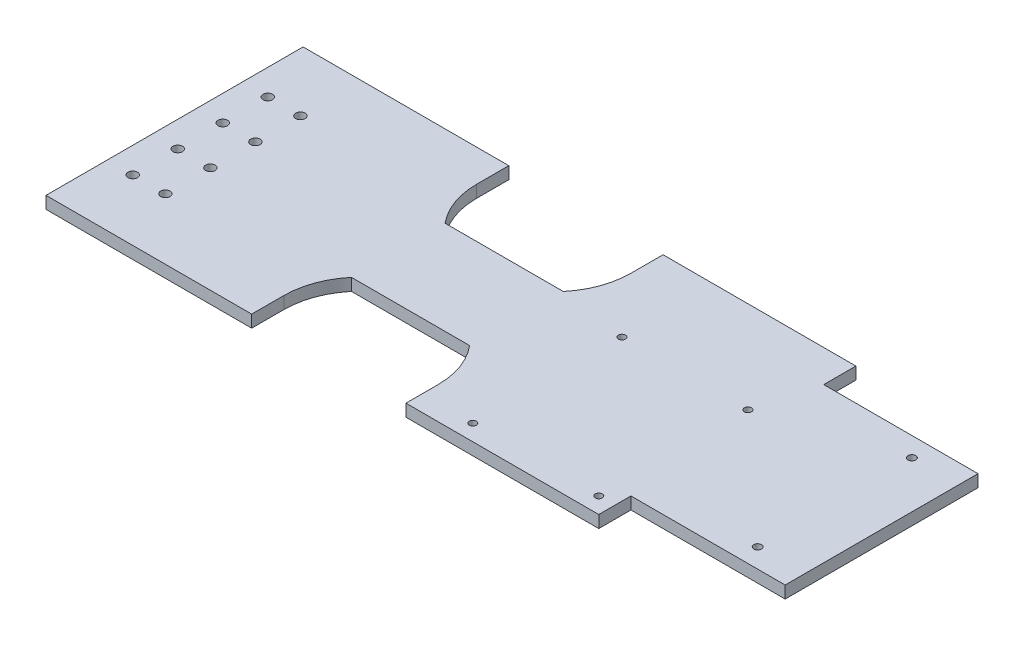
SolidWorks part; units mm, degrees
ref_plane "Front Plane" through (0, 0, 0) normal (0, 0, 1) x (1, 0, 0)
ref_plane "Top Plane" through (0, 0, 0) normal (0, 1, 0) x (1, 0, 0)
ref_plane "Right Plane" through (0, 0, 0) normal (1, 0, 0) x (0, 0, -1)
sketch "Sketch1" plane through (0, 0, 0) normal (0, 1, 0) x (1, 0, 0)
  line L0 (0, 0) -> (137.5, 0) construction
  line L1 (-137.5, 50) -> (137.5, 50)
  line L2 (-137.5, 50) -> (-137.5, -50)
  line L3 (-137.5, -50) -> (137.5, -50)
  line L4 (137.5, 50) -> (137.5, -50)
  line L5 (-137.5, 50) -> (137.5, -50) construction
  line L6 (-137.5, -50) -> (137.5, 50) construction
  point P0 (0, 0)
  point P11 (119.5, 0)
  point P14 (107, 0)
  point P19 (107, 0)
  dimension "D4" = 18
  dimension "D1" = 275
  dimension "D2" = 100
extrude "Boss-Extrude4" add sketch "Sketch1" along normal blind 4.75
sketch "Sketch3" plane through (0, 4.75, 0) normal (0, 1, 0) x (1, 0, 0)
  line L0 (0, 0) -> (137.5, 0) construction
  line L1 (137.5, -50) -> (137.5, 50) construction
  line L2 (119.3, -31.5) -> (119.3, 31.5) construction
  line L3 (137.5, -50) -> (77.5, -50)
  line L4 (137.5, -50) -> (137.5, -37.5)
  line L5 (137.5, -37.5) -> (77.5, -37.5)
  line L6 (77.5, -50) -> (77.5, -37.5)
  line L7 (137.5, 50) -> (77.5, 50)
  line L8 (137.5, 50) -> (137.5, 37.5)
  line L9 (137.5, 37.5) -> (77.5, 37.5)
  line L10 (77.5, 50) -> (77.5, 37.5)
  line L11 (119.3, -30) -> (119.3, 30) construction
  line L12 (-137.5, -50) -> (137.5, -50) construction
  line L13 (2.5, -50) -> (-57.5, -50)
  line L14 (2.5, -50) -> (2.5, -37.5)
  line L16 (-57.5, -50) -> (-57.5, -37.5)
  line L17 (137.5, 50) -> (-137.5, 50) construction
  line L18 (2.5, 50) -> (-57.5, 50)
  line L19 (2.5, 50) -> (2.5, 37.5)
  line L21 (-57.5, 50) -> (-57.5, 37.5)
  line L22 (-27.5, -37.5) -> (-27.5, -50) construction
  line L23 (-27.5, 37.5) -> (-27.5, 50) construction
  line L24 (-4.5187, 18.2164) -> (-50.4813, 18.2164)
  line L25 (-50.4813, -18.2164) -> (-4.5187, -18.2164)
  circle A0 centre (119.3, -30) radius 1.5
  circle A2 centre (119.3, 30) radius 1.5
  arc A5 (2.5, 37.5) -> (-4.5187, 18.2164) centre (-27.5, 37.5) cw
  arc A6 (-57.5, 37.5) -> (-50.4813, 18.2164) centre (-27.5, 37.5) ccw
  arc A7 (2.5, -37.5) -> (-4.5187, -18.2164) centre (-27.5, -37.5) ccw
  arc A8 (-57.5, -37.5) -> (-50.4813, -18.2164) centre (-27.5, -37.5) cw
  point P24 (119.3, 0)
  point P35 (119.3, 0)
  dimension "D1" = 75
  dimension "D2" = 60
  dimension "D3" = 60
  dimension "D4" = 63
  dimension "D5" = 18.2
  dimension "D7" = 75
extrude "Cut-Extrude1" cut sketch "Sketch3" against normal blind 10
sketch "Sketch4" plane through (0, 4.75, 0) normal (0, 1, 0) x (1, 0, 0)
  line L0 (-137.5, -50) -> (-57.5, -50) construction
  line L1 (-137.5, 50) -> (-137.5, -50) construction
  line L2 (-127.5, -26.25) -> (-114.8, -26.25) construction
  line L3 (-97.1256, -34.9967) -> (-84.4256, -34.9967) construction
  line L4 (-127.5, -26.25) -> (-127.5, -50) construction
  line L5 (-127.5, -26.25) -> (-127.5, 26.25) construction
  line L6 (-127.5, 26.25) -> (-127.5, 50) construction
  line L7 (77.5, 50) -> (2.5, 50) construction
  line L8 (-127.5, 26.25) -> (-114.8, 26.25) construction
  line L9 (-114.8, -26.25) -> (-114.8, -8.75) construction
  line L10 (-114.8, 8.75) -> (-114.8, 26.25) construction
  line L11 (-114.8, -8.75) -> (-127.5, -8.75) construction
  line L12 (-114.8, 8.75) -> (-127.5, 8.75) construction
  line L13 (-114.8, -8.75) -> (-114.8, 8.75) construction
  line L14 (2.5, -50) -> (77.5, -50) construction
  line L17 (77.5, -37.5) -> (77.5, -50) construction
  line L18 (71.25, -43.75) -> (8.0809, -43.75) construction
  line L19 (71.25, -43.75) -> (71.25, 43.9397) construction
  line L20 (22.25, -43.75) -> (22.25, 28.7684) construction
  line L21 (71.25, 14.25) -> (12.3286, 14.25) construction
  circle A0 centre (-127.5, -26.25) radius 1.85
  circle A1 centre (-114.8, -26.25) radius 1.85
  circle A2 centre (-127.5, -8.75) radius 1.85
  circle A3 centre (-114.8, -8.75) radius 1.85
  circle A4 centre (-114.8, 8.75) radius 1.85
  circle A5 centre (-127.5, 8.75) radius 1.85
  circle A6 centre (-114.8, 26.25) radius 1.85
  circle A7 centre (-127.5, 26.25) radius 1.85
  circle A8 centre (71.25, -43.75) radius 1.375
  circle A9 centre (22.25, -43.75) radius 1.375
  circle A10 centre (71.25, 14.25) radius 1.375
  circle A11 centre (22.25, 14.25) radius 1.375
  dimension "D1" = 3.7
  dimension "D8" = 2.75
  dimension "D2" = 12.7
  dimension "D3" = 17.5
  dimension "D4" = 10
  dimension "D5" = 17.5
  dimension "D6" = 6.25
  dimension "D7" = 6.25
  dimension "D9" = 49
  dimension "D10" = 58
extrude "Cut-Extrude2" cut sketch "Sketch4" against normal blind 10
